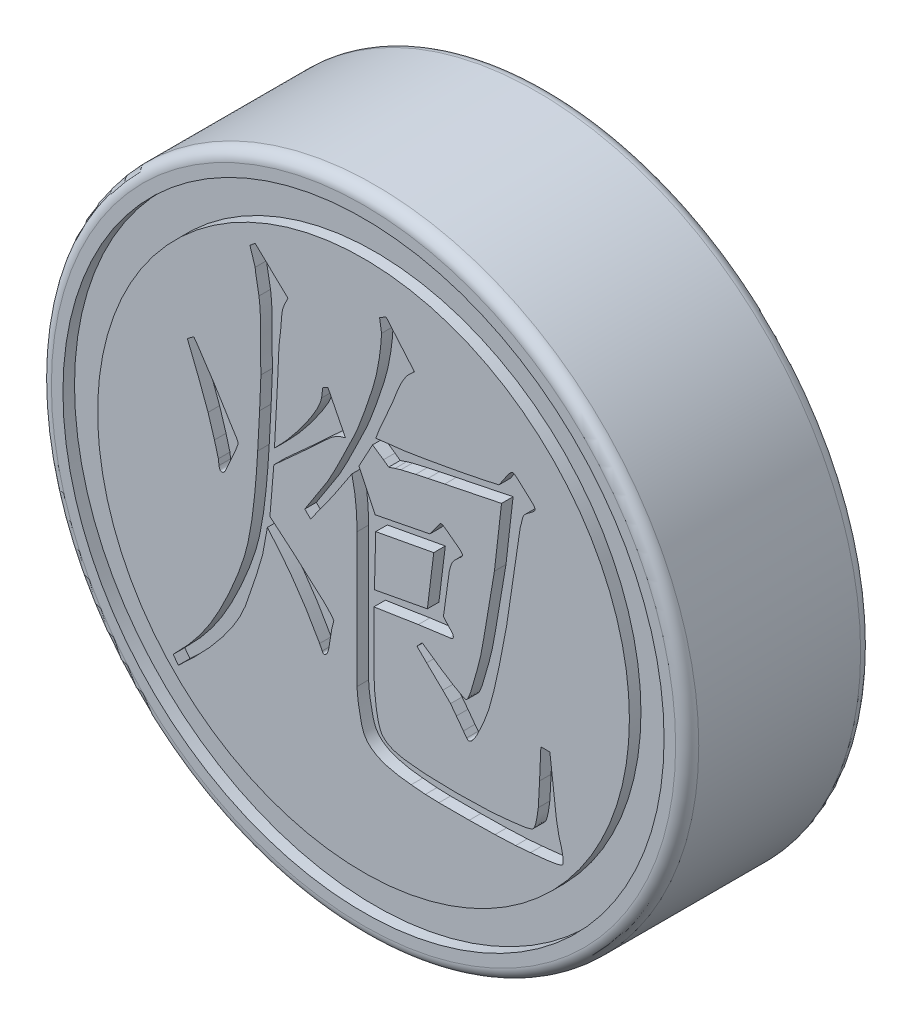
SolidWorks part; units mm, degrees
ref_plane "前视基准面" through (0, 0, 0) normal (0, 0, 1) x (1, 0, 0)
ref_plane "上视基准面" through (0, 0, 0) normal (0, 1, 0) x (1, 0, 0)
ref_plane "右视基准面" through (0, 0, 0) normal (1, 0, 0) x (0, 0, -1)
sketch "草图1" plane through (0, 0, 0) normal (0, 0, 1) x (1, 0, 0)
  circle A0 centre (0, 0) radius 14
extrude "凸台-拉伸1" add sketch "草图1" along normal blind 8
sketch "草图2" plane through (0, 0, 8) normal (0, 0, 1) x (1, 0, 0)
  circle A0 centre (0, 0) radius 13
  circle A1 centre (0, 0) radius 11.5
extrude "切除-拉伸1" cut sketch "草图2" against normal blind 0.5
sketch "草图3" plane through (0, 0, 0) normal (0, 0, -1) x (-1, 0, 0)
  circle A0 centre (0, 0) radius 5.1
extrude "切除-拉伸2" cut sketch "草图3" against normal blind 5
chamfer "倒角1" distance 0.5 angle 45 1 edges at (-5.1, 0, 0)
fillet "圆角1" radius 0.5 2 edges at (14, 0, 8) (14, 0, 0)
sketch "草图4" plane through (0, 0, 8) normal (0, 0, 1) x (1, 0, 0)
  text T0 "炮" font "汉仪长仿宋体" height 13
extrude "切除-拉伸3" cut sketch "草图4" against normal blind 0.5
